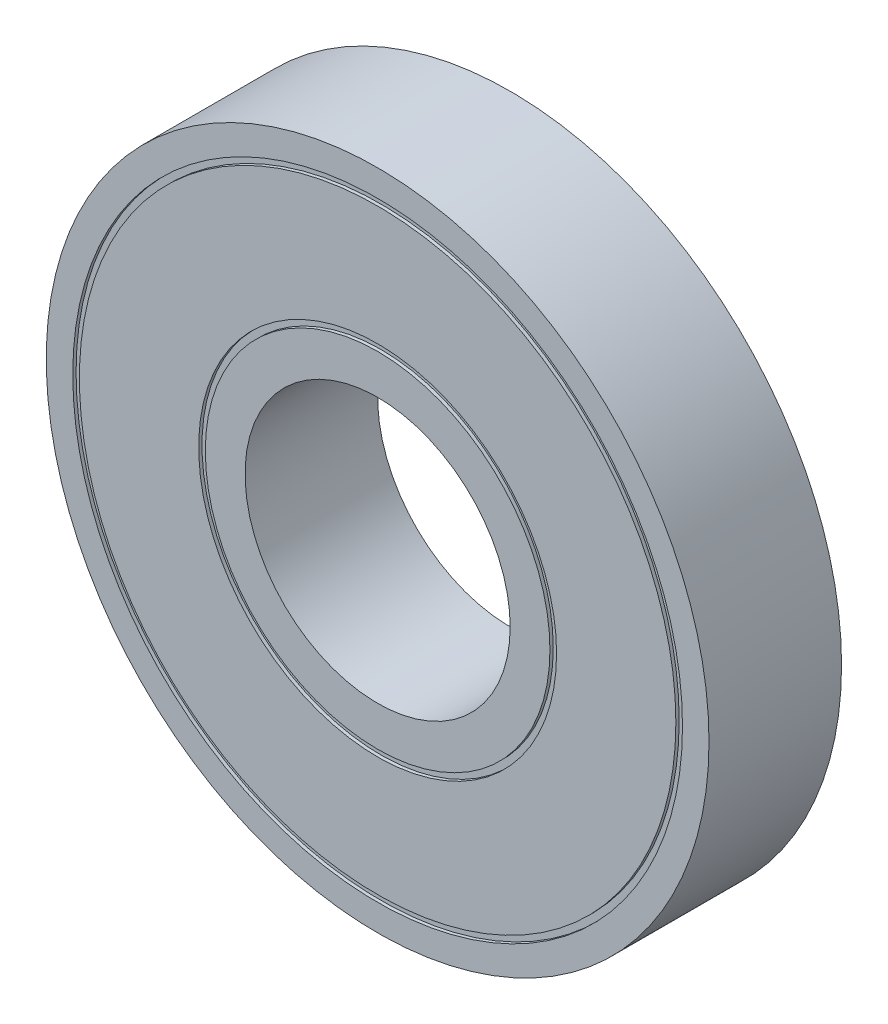
SolidWorks part; units mm, degrees
material "ASTM A36 Aço"
ref_plane "Plano frontal" through (0, 0, 0) normal (0, 0, 1) x (1, 0, 0)
ref_plane "Plano superior" through (0, 0, 0) normal (0, 1, 0) x (1, 0, 0)
ref_plane "Plano direito" through (0, 0, 0) normal (1, 0, 0) x (0, 0, -1)
sketch "Esboço1" plane through (0, 0, 0) normal (0, 0, 1) x (1, 0, 0)
  circle A0 centre (0, 0) radius 10
  circle A1 centre (0, 0) radius 25
  dimension "D1" = 20
  dimension "D2" = 50
extrude "Ressalto-extrusão1" add sketch "Esboço1" along normal mid plane 10
sketch "Esboço2" plane through (0, 0, 5) normal (0, 0, 1) x (1, 0, 0)
  circle A0 centre (0, 0) radius 23
  circle A1 centre (0, 0) radius 25
  circle A2 centre (0, 0) radius 25
  circle A3 centre (0, 0) radius 22.5
  circle A4 centre (0, 0) radius 13.5
  circle A5 centre (0, 0) radius 13
  circle A6 centre (0, 0) radius 13
  dimension "D1" = 0
  dimension "D2" = 3
  dimension "D3" = 0.5
  dimension "D4" = 2
  dimension "D5" = 0.5
extrude "Corte-extrusão1" cut sketch "Esboço2" against normal blind 0.25 contours A4 A6 | A0 A3
mirror "Espelhar1" about plane through (0, 0, 0) normal (0, 0, 1) of "Corte-extrusão1"
